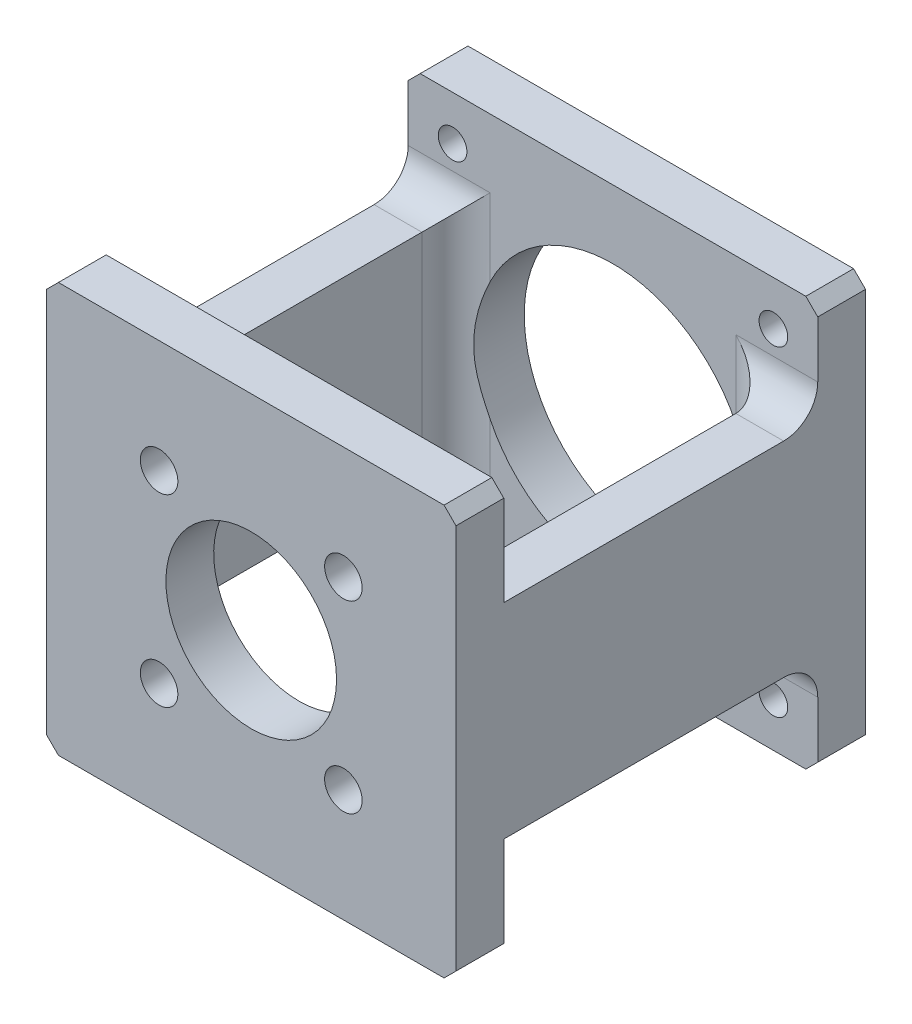
SolidWorks part; units mm, degrees
ref_plane "Front Plane" through (0, 0, 0) normal (0, 0, 1) x (1, 0, 0)
ref_plane "Top Plane" through (0, 0, 0) normal (0, 1, 0) x (1, 0, 0)
ref_plane "Right Plane" through (0, 0, 0) normal (1, 0, 0) x (0, 0, -1)
sketch "Sketch1" plane through (0, 0, 0) normal (1, 0, 0) x (0, 0, -1)
  line L0 (-30, -30) -> (-30, 30)
  line L1 (-30, 30) -> (-23, 30)
  line L2 (-23, 30) -> (-23, 15)
  line L3 (-23, 15) -> (23, 15)
  line L4 (0, 15) -> (0, -15) construction
  line L5 (23, -15) -> (-23, -15)
  line L6 (-23, -15) -> (-23, -30)
  line L7 (-23, -30) -> (-30, -30)
  line L8 (23, -30) -> (30, -30)
  line L9 (23, -15) -> (23, -30)
  line L10 (23, 30) -> (23, 15)
  line L11 (30, 30) -> (23, 30)
  line L12 (30, -30) -> (30, 30)
  point P3 (0, 0)
  point P10 (-30, 0)
  dimension "D1" = 30
  dimension "D2" = 60
  dimension "D3" = 7
  dimension "D4" = 60
extrude "Boss-Extrude1" add sketch "Sketch1" along normal mid plane 60
sketch "Sketch2" plane through (0, 0, 0) normal (0, 1, 0) x (1, 0, 0)
  line L0 (30, -23) -> (-30, -23) construction
  line L1 (23, -23) -> (-23, -23)
  line L2 (23, -23) -> (23, 23)
  line L3 (23, 23) -> (-23, 23)
  line L4 (-23, -23) -> (-23, 23)
  line L5 (30, 23) -> (-30, 23) construction
  line L6 (-30, 23) -> (-30, -23) construction
  line L7 (30, 23) -> (30, -23) construction
  dimension "D1" = 7
  dimension "D2" = 7
extrude "Cut-Extrude1" cut sketch "Sketch2" against normal through all both and the other way through all
fillet "Fillet1" radius 5 6 edges at (26.5, -15, -23) (-26.5, -15, -23) (26.5, 15, -23) (23, 0, -23) (-26.5, 15, -23) (-23, 0, -23)
chamfer "Chamfer1" distance 1.75 angle 45 8 edges at (-30, -30, -26.5) (-30, -30, 26.5) (-30, 30, -26.5) (-30, 30, 26.5) (30, -30, -26.5) (30, -30, 26.5) (30, 30, -26.5) (30, 30, 26.5)
hole_wizard "M5x0.8 Tapped Hole1" positions "Sketch4" profile "Sketch7" tap size "M5x0.8" standard "ANSI Metric"
sketch "Sketch4" plane through (0, 0, -30) normal (0, 0, -1) x (-1, 0, 0)
  line L1 (-23.5, -23.5) -> (23.5, -23.5)
  line L2 (-23.5, -23.5) -> (-23.5, 23.5)
  line L3 (-23.5, 23.5) -> (23.5, 23.5)
  line L4 (23.5, -23.5) -> (23.5, 23.5)
  line L7 (0, 0) -> (23.5, 0) construction
  line L9 (0, 0) -> (0, 23.5) construction
  point P0 (-23.5, 23.5)
  point P2 (23.5, 23.5)
  point P4 (23.5, -23.5)
  point P6 (-23.5, -23.5)
  dimension "D1" = 47
sketch "Sketch7" plane through (23.5, 23.5, -30) normal (1, 0, 0) x (0, 1, 0)
  line L0 (0, 0) -> (0, 7)
  line L1 (0, 7) -> (2.1, 7)
  line L2 (2.1, 7) -> (2.1, 0)
  line L5 (2.1, 0) -> (0, 0)
  line L11 (0, -6.35) -> (0, 107.95) construction
  dimension "Thru Tap Drill Dia." = 4.2
  dimension "Thru Tap Drill Depth" = 7
cosmetic thread "Hole Thread1" parameters "D2"=5
cosmetic thread "Hole Thread2" parameters "D2"=5
cosmetic thread "Hole Thread3" parameters "D2"=5
cosmetic thread "Hole Thread4" parameters "D2"=5
hole_wizard "M5 Clearance Hole1" positions "Sketch8" profile "Sketch10" hole size "M5" standard "ANSI Metric"
sketch "Sketch8" plane through (0, 0, 30) normal (0, 0, 1) x (1, 0, 0)
  line L0 (-13.5, 13.5) -> (13.5, 13.5) construction
  line L1 (13.5, 13.5) -> (13.5, -13.5) construction
  line L2 (13.5, -13.5) -> (-13.5, -13.5) construction
  line L3 (-13.5, -13.5) -> (-13.5, 13.5) construction
  line L5 (0, 0) -> (-13.5, 0)
  line L7 (0, 0) -> (0, 13.5)
  point P0 (-13.5, 13.5)
  point P2 (-13.5, -13.5)
  point P4 (13.5, -13.5)
  point P6 (13.5, 13.5)
  point P28 (0, 0)
  dimension "D1" = 27
sketch "Sketch10" plane through (-13.5, 13.5, 30) normal (1, 0, 0) x (0, -1, 0)
  line L0 (0, 0) -> (0, 7)
  line L1 (0, 7) -> (2.75, 7)
  line L2 (2.75, 7) -> (2.75, 0)
  line L5 (2.75, 0) -> (0, 0)
  line L11 (0, -6.35) -> (0, 107.95) construction
  dimension "Thru Hole Dia." = 5.5
  dimension "Thru Hole Depth" = 7
sketch "Sketch11" plane through (0, 0, 0) normal (0, 0, 1) x (1, 0, 0)
  line L0 (28.25, 30) -> (-28.25, 30) construction
  circle A0 centre (0, 0) radius 12.5
  point P3 (0, 12.5)
  dimension "D1" = 17.5
extrude "Cut-Extrude2" cut sketch "Sketch11" along normal through all
sketch "Sketch12" plane through (0, 0, 0) normal (0, 0, 1) x (1, 0, 0)
  line L0 (28.25, 30) -> (-28.25, 30) construction
  circle A0 centre (0, 0) radius 20
  point P3 (0, 20)
  dimension "D1" = 10
extrude "Cut-Extrude3" cut sketch "Sketch12" against normal through all
